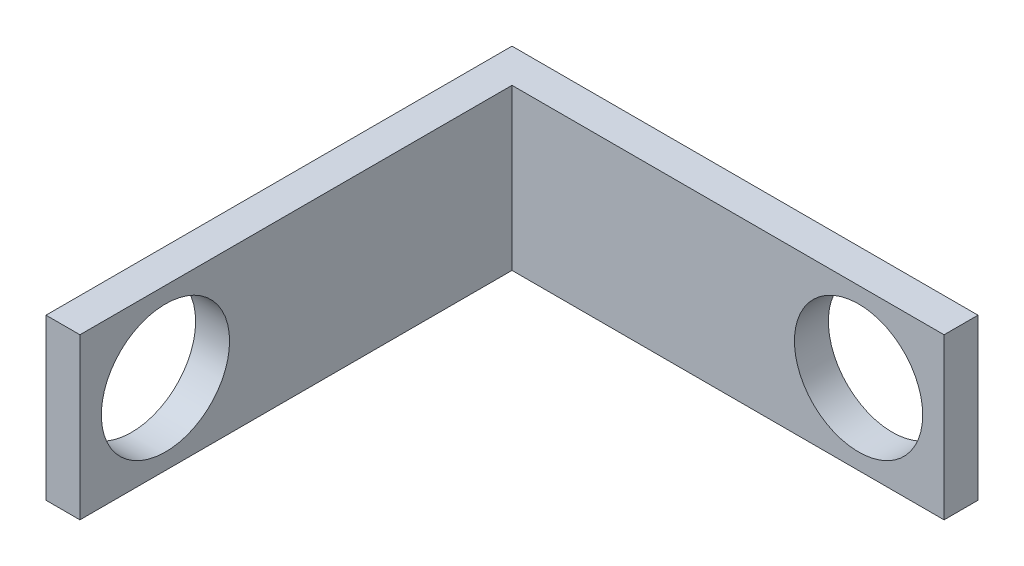
SolidWorks part; units mm, degrees
ref_plane "Front Plane" through (0, 0, 0) normal (0, 0, 1) x (1, 0, 0)
ref_plane "Top Plane" through (0, 0, 0) normal (0, 1, 0) x (1, 0, 0)
ref_plane "Right Plane" through (0, 0, 0) normal (1, 0, 0) x (0, 0, -1)
sketch "Sketch1" plane through (0, 0, 0) normal (0, 1, 0) x (1, 0, 0)
  line L0 (-17.0063, 0) -> (0, 0) construction
  line L1 (-4, 16.2125) -> (4, 16.2125)
  line L2 (-4, 16.2125) -> (-4, 17.8) construction
  line L3 (-4, 17.8) -> (4, 17.8)
  line L4 (4, 16.2125) -> (4, 17.8)
  line L5 (-4, 16.2125) -> (4, 17.8) construction
  line L6 (-4, 17.8) -> (4, 16.2125) construction
  line L7 (-17.8, 4) -> (-16.2125, 4) construction
  line L8 (-17.8, 4) -> (-17.8, -4)
  line L9 (-17.8, -4) -> (-16.2125, -4)
  line L10 (-16.2125, 4) -> (-16.2125, -4)
  line L11 (-17.8, 4) -> (-16.2125, -4) construction
  line L12 (-17.8, -4) -> (-16.2125, 4) construction
  line L13 (0, 0) -> (0, 17.0063) construction
  line L14 (-16.2125, 4) -> (-16.2125, 16.2125)
  line L15 (-16.2125, 16.2125) -> (-4, 16.2125)
  line L16 (-17.8, 4) -> (-17.8, 17.8)
  line L17 (-17.8, 17.8) -> (-4, 17.8)
  arc A0 (-16.2125, 4) -> (-4, 16.2125) centre (-4, 4) cw construction
  arc A1 (-17.8, 4) -> (-4, 17.8) centre (-4, 4) cw construction
  point P0 (0, 17.0063)
  point P5 (-17.0063, 0)
  dimension "D3" = 21.8
  dimension "D1" = 1.5875
  dimension "D2" = 8
extrude "Boss-Extrude1" add sketch "Sketch1" along normal mid plane 7.5 contours L10 L7 L8 L9 | L1 L4 L3 L2
sketch "Sketch2" plane through (0, 0, -16.2125) normal (0, 0, 1) x (1, 0, 0)
  circle A0 centre (0, 0) radius 3
  dimension "D1" = 6
extrude "Cut-Extrude1" cut sketch "Sketch2" against normal through all
sketch "Sketch3" plane through (-16.2125, 0, 0) normal (1, 0, 0) x (0, 0, -1)
  circle A0 centre (0, 0) radius 3
  dimension "D1" = 6
extrude "Cut-Extrude2" cut sketch "Sketch3" against normal through all
